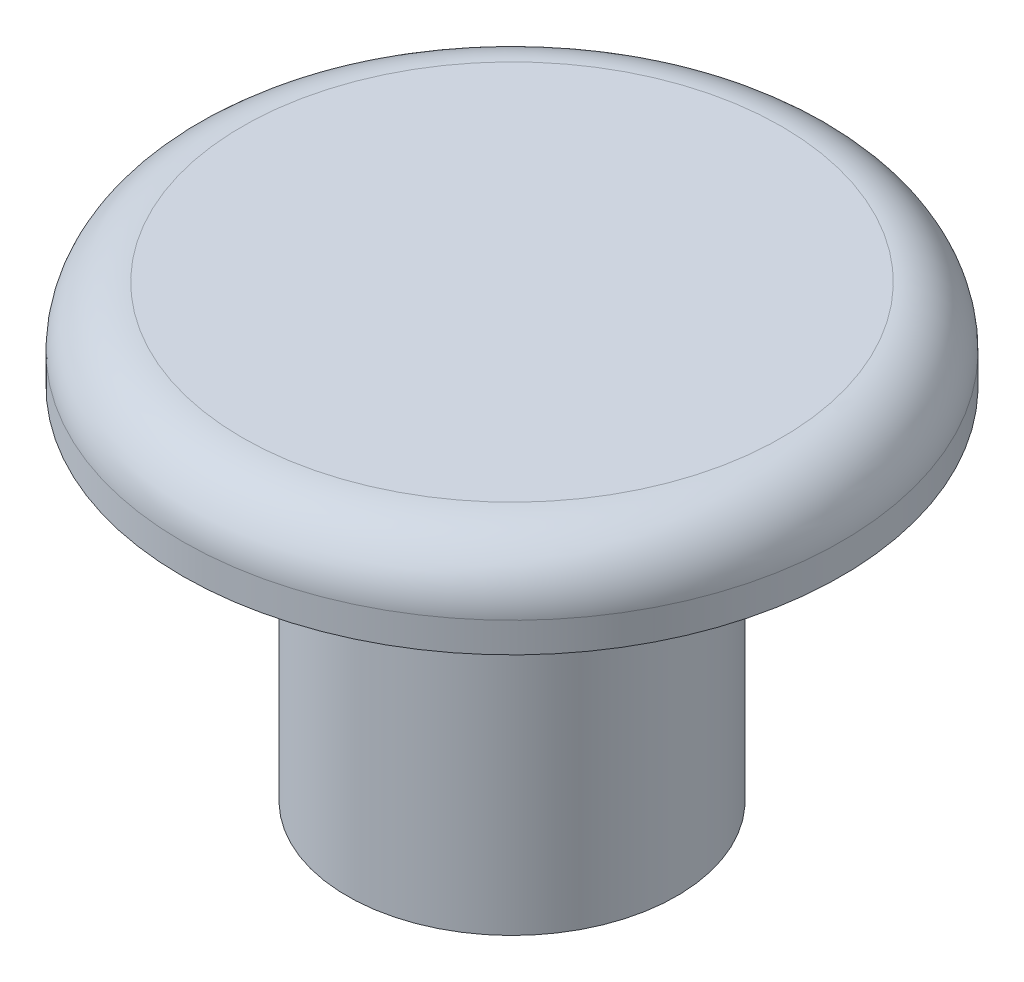
SolidWorks part; units mm, degrees
ref_plane "Front Plane" through (0, 0, 0) normal (0, 0, 1) x (1, 0, 0)
ref_plane "Top Plane" through (0, 0, 0) normal (0, 1, 0) x (1, 0, 0)
ref_plane "Right Plane" through (0, 0, 0) normal (1, 0, 0) x (0, 0, -1)
sketch "Sketch1" plane through (0, 0, 0) normal (0, 1, 0) x (1, 0, 0)
  circle A0 centre (0, 0) radius 11
  dimension "D1" = 22
extrude "Boss-Extrude1" add sketch "Sketch1" along normal blind 3
fillet "Fillet1" radius 2 1 edges at (0, 3, 11)
sketch "Sketch2" plane through (0, 0, 0) normal (0, -1, 0) x (1, 0, 0)
  circle A0 centre (0, 0) radius 5.5
  dimension "D1" = 11
extrude "Boss-Extrude2" add sketch "Sketch2" along normal blind 12
